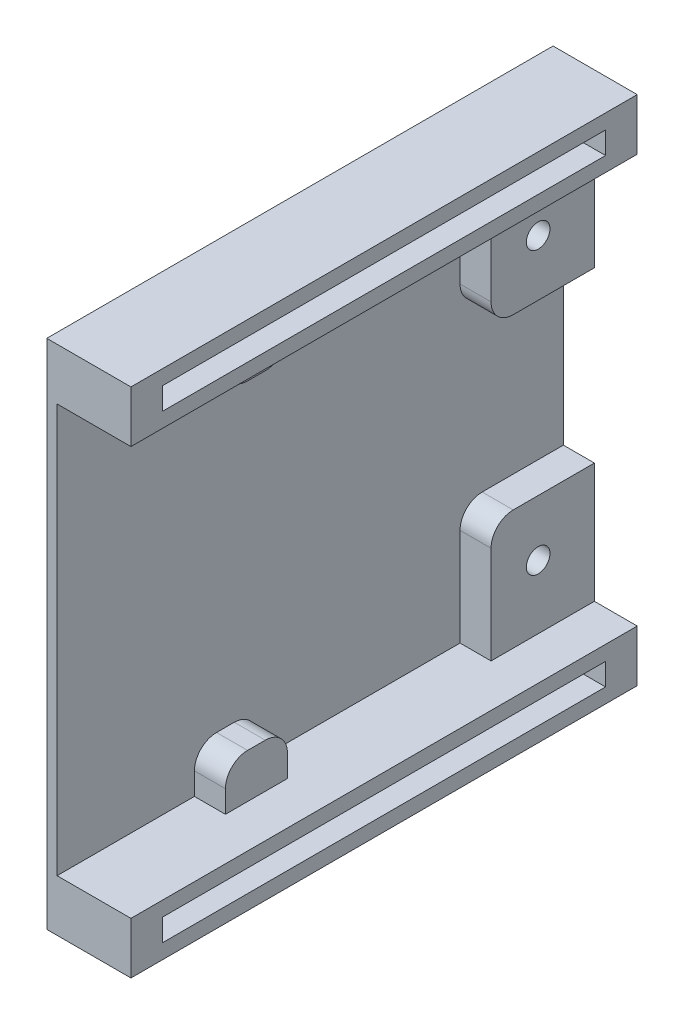
SolidWorks part; units mm, degrees
ref_plane "Front Plane" through (0, 0, 0) normal (1, 0, 0) x (0, 1, 0)
ref_plane "Top Plane" through (0, 0, 0) normal (0, 0, 1) x (0, 1, 0)
ref_plane "Right Plane" through (0, 0, 0) normal (0, 1, 0) x (-1, 0, 0)
sketch "Sketch1" plane through (0, 0, 0) normal (1, 0, 0) x (0, 1, 0)
  line L5 (-17.335, 17.145) -> (17.335, 17.145)
  line L7 (-17.335, 17.145) -> (-17.335, -17.145)
  line L8 (-17.335, -17.145) -> (17.335, -17.145)
  line L9 (17.335, 17.145) -> (17.335, -17.145)
  line L10 (-17.335, 17.145) -> (17.335, -17.145) construction
  line L11 (-17.335, -17.145) -> (17.335, 17.145) construction
  line L12 (-13.335, 17.145) -> (13.335, 17.145) construction
  line L13 (-13.335, 17.145) -> (-13.335, -17.145) construction
  line L14 (-13.335, -17.145) -> (13.335, -17.145) construction
  line L15 (13.335, 17.145) -> (13.335, -17.145) construction
  line L16 (-13.335, 17.145) -> (13.335, -17.145) construction
  line L17 (-13.335, -17.145) -> (13.335, 17.145) construction
  point P0 (0, 0)
  point P6 (0, 0)
  dimension "D1" = 34.67
  dimension "D2" = 34.29
  dimension "D3" = 34.29
  dimension "D4" = 26.67
extrude "Boss-Extrude1" add sketch "Sketch1" along normal blind 1
sketch "Sketch3" plane through (1, 0, 0) normal (1, 0, 0) x (0, 1, 0)
  line L0 (-17.335, -17.145) -> (17.335, -17.145) construction
  line L1 (-17.335, 17.145) -> (-13.835, 17.145)
  line L2 (-17.335, 17.145) -> (-17.335, -17.145)
  line L3 (-17.335, -17.145) -> (-13.835, -17.145)
  line L4 (-13.835, 17.145) -> (-13.835, -17.145)
  line L5 (17.335, 17.145) -> (-17.335, 17.145) construction
  line L6 (17.335, -17.145) -> (13.835, -17.145)
  line L7 (17.335, -17.145) -> (17.335, 17.145)
  line L8 (17.335, 17.145) -> (13.835, 17.145)
  line L9 (13.835, -17.145) -> (13.835, 17.145)
  line M3 (17.335, -17.145) -> (17.335, 17.145)
  line M4 (17.335, 17.145) -> (-17.335, 17.145)
  line M5 (-17.335, 17.145) -> (-17.335, -17.145)
  line M6 (-17.335, -17.145) -> (17.335, -17.145)
  dimension "D1" = 3.5
extrude "Boss-Extrude2" add sketch "Sketch3" along normal blind 5 contours L4 M4 M5 M6 | L9 M6 M3 M4
sketch "Sketch5" plane through (6, 0, 0) normal (1, 0, 0) x (0, 1, 0)
  line L0 (0, 0) -> (0, 50000) construction
  line L1 (-16.335, -15) -> (-14.835, -15)
  line L2 (-16.335, -15) -> (-16.335, 15)
  line L3 (-16.335, 15) -> (-14.835, 15)
  line L4 (-14.835, -15) -> (-14.835, 15)
  line L5 (-16.335, -15) -> (-14.835, 15) construction
  line L6 (-16.335, 15) -> (-14.835, -15) construction
  line L7 (-17.335, 0) -> (-15.585, 0) construction
  line L8 (-17.335, 17.145) -> (-17.335, -17.145) construction
  line L9 (-15.585, 0) -> (-13.835, 0) construction
  line L10 (-13.835, 17.145) -> (-13.835, -17.145) construction
  line L11 (15.585, 0) -> (13.835, 0) construction
  line L12 (17.335, 0) -> (15.585, 0) construction
  line L13 (16.335, 15) -> (14.835, -15) construction
  line L14 (16.335, -15) -> (14.835, 15) construction
  line L15 (14.835, -15) -> (14.835, 15)
  line L16 (16.335, 15) -> (14.835, 15)
  line L17 (16.335, -15) -> (16.335, 15)
  line L18 (16.335, -15) -> (14.835, -15)
  point P0 (-15.585, 0)
  point P22 (15.585, 0)
  dimension "D1" = 1.5
  dimension "D2" = 30
extrude "Cut-Extrude1" cut sketch "Sketch5" against normal through all both and the other way through all
sketch "Sketch6" plane through (1, 0, 0) normal (1, 0, 0) x (0, 1, 0)
  line L0 (-13.835, 17.145) -> (-13.835, -17.145) construction
  line L1 (-13.835, 7.845) -> (-10.835, 7.845)
  line L2 (-13.835, 7.845) -> (-13.835, 3.645)
  line L3 (-13.835, 3.645) -> (-10.835, 3.645)
  line L4 (-10.835, 7.845) -> (-10.835, 3.645)
  line L5 (0, 0) -> (0, -49383.4727) construction
  line L6 (-13.835, -17.145) -> (-5.725, -17.145)
  line L7 (-13.835, -17.145) -> (-13.835, -10.145)
  line L8 (-13.835, -10.145) -> (-5.725, -10.145)
  line L9 (-5.725, -17.145) -> (-5.725, -10.145)
  line L10 (13.835, 17.145) -> (-13.835, 17.145) construction
  line L11 (5.725, -17.145) -> (5.725, -10.145)
  line L12 (13.835, -10.145) -> (5.725, -10.145)
  line L13 (13.835, -17.145) -> (13.835, -10.145)
  line L14 (13.835, -17.145) -> (5.725, -17.145)
  line L15 (10.835, 7.845) -> (10.835, 3.645)
  line L16 (13.835, 3.645) -> (10.835, 3.645)
  line L17 (13.835, 7.845) -> (13.835, 3.645)
  line L18 (13.835, 7.845) -> (10.835, 7.845)
  dimension "D1" = 5.725
  dimension "D2" = 7
  dimension "D3" = 9.3
  dimension "D4" = 13.5
  dimension "D5" = 3
extrude "Boss-Extrude3" add sketch "Sketch6" along normal blind 2.1
fillet "Fillet1" radius 1.5 6 edges at (2.05, 10.835, 3.645) (2.05, 10.835, 7.845) (2.05, -10.835, 3.645) (2.05, -10.835, 7.845) (2.05, 5.725, -10.145) (2.05, -5.725, -10.145)
sketch "Sketch7" plane through (3.1, 0, 0) normal (1, 0, 0) x (0, 1, 0)
  line L0 (0, 0) -> (0, -50000) construction
  line L2 (-13.835, -17.145) -> (-5.725, -17.145) construction
  circle A0 centre (-9.525, -13.335) radius 0.8
  circle A1 centre (9.525, -13.335) radius 0.8
  dimension "D3" = 1.6
  dimension "D1" = 3.81
  dimension "D2" = 9.525
extrude "Cut-Extrude2" cut sketch "Sketch7" against normal through all both and the other way through all contours A0 | A1
chamfer "Chamfer1" distance 0.3 angle 45 14 edges at (0, -9.525, -14.135) (0, 9.525, -14.135) (0, -16.335, 0) (0, -15.585, 15) (0, -14.835, 0) (0, -15.585, -15) (0, 14.835, 0) (0, 15.585, 15) (0, 16.335, 0) (0, 15.585, -15) (0, 0, 17.145) (0, -17.335, 0) (0, 0, -17.145) (0, 17.335, 0)
equation "\"PCB_Width\"= 1.05in"
equation "\"PCB_Length\"= 1.35in"
equation "\"PCB_Thickness\"= 1.50404mm"
equation "\"USB_Height\"= 3.36mm"
equation "\"ZIF_Height\"= 2mm"
equation "\"Case_Thickness\"= 5mm"
